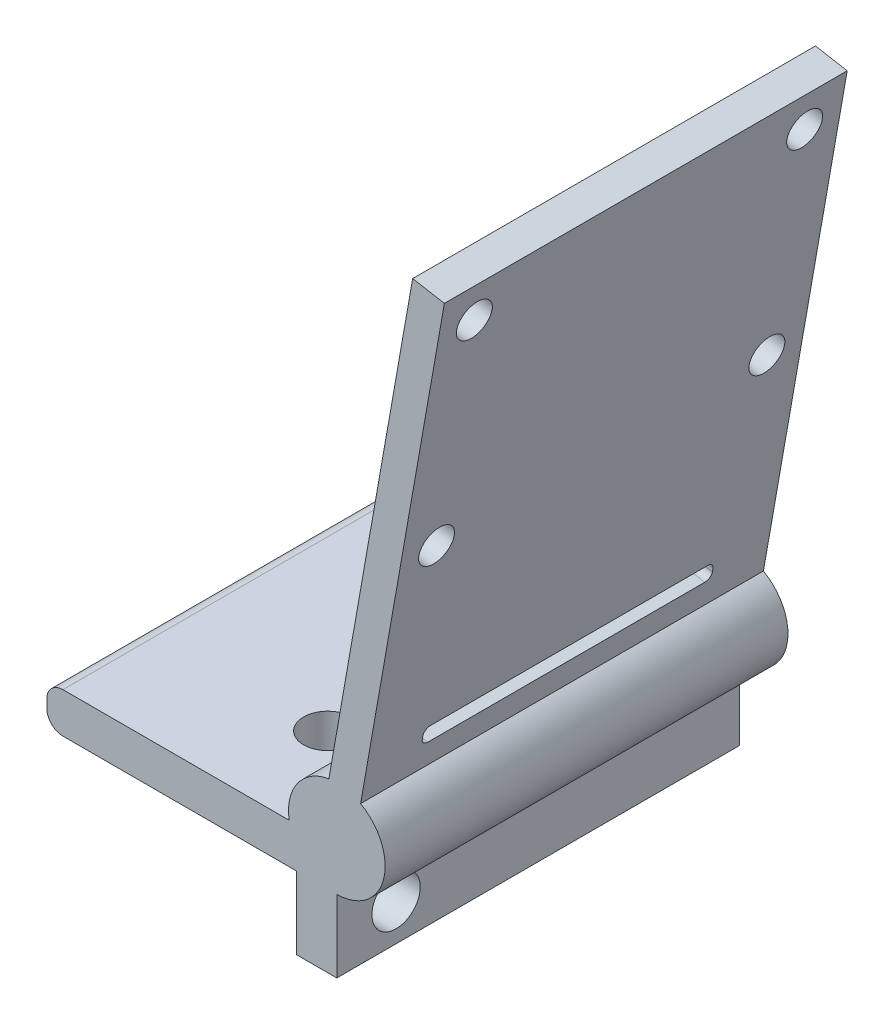
SolidWorks part; units mm, degrees
ref_plane "Front Plane" through (0, 0, 0) normal (0, 0, 1) x (1, 0, 0)
ref_plane "Top Plane" through (0, 0, 0) normal (0, 1, 0) x (1, 0, 0)
ref_plane "Right Plane" through (0, 0, 0) normal (1, 0, 0) x (0, 0, -1)
sketch "Sketch1" plane through (0, 0, 0) normal (0, 0, 1) x (1, 0, 0)
  line L0 (0, -3) -> (0, -0.5)
  line L1 (0, -3) -> (-17, -3)
  line L2 (0, -0.5) -> (-17, -0.5)
  line L3 (-18, -2) -> (-18, -1.5)
  line L4 (6.6753, 32.0985) -> (0.9848, -0.1736)
  line L5 (6.6753, 32.0985) -> (4.7056, 32.4458)
  line L6 (0.9848, -0.1736) -> (-0.9848, 0.1736)
  line L7 (4.7056, 32.4458) -> (-0.9848, 0.1736)
  line L8 (6.6753, 32.0985) -> (-0.9848, 0.1736) construction
  line L9 (0.9848, -0.1736) -> (4.7056, 32.4458) construction
  line L10 (2.8452, 16.1361) -> (0, 0)
  circle A0 centre (0, 0) radius 3
  arc A1 (-18, -2) -> (-17, -3) centre (-17, -2) ccw
  arc A2 (-17, -0.5) -> (-18, -1.5) centre (-17, -1.5) ccw
  point P9 (-18, -3)
  point P13 (2.8452, 16.1361)
  point P19 (0, 0)
  dimension "D1" = 6
  dimension "D4" = 1
  dimension "D5" = 1
  dimension "D2" = 2.5
  dimension "D3" = 18
  dimension "D6" = 2
  dimension "D7" = 32.77
  dimension "D8" = 100
extrude "Boss-Extrude2" add sketch "Sketch1" along normal mid plane 25
sketch "Sketch2" plane through (0.9848, -0.1736, 0) normal (0.9848, -0.1736, 0) x (0, 0, -1)
  line L0 (-12.5, 2.8284) -> (12.5, 2.8284) construction
  line L1 (-8.6, 4.3284) -> (8.6, 4.3284)
  line L2 (-9, 4.7284) -> (-9, 4.9284)
  line L3 (-8.6, 5.3284) -> (8.6, 5.3284)
  line L4 (9, 4.7284) -> (9, 4.9284)
  line L5 (-12.5, 32.77) -> (-12.5, 2.8284) construction
  arc A0 (-8.6, 5.3284) -> (-9, 4.9284) centre (-8.6, 4.9284) ccw
  arc A1 (-8.6, 4.3284) -> (-9, 4.7284) centre (-8.6, 4.7284) cw
  arc A2 (8.6, 5.3284) -> (9, 4.9284) centre (8.6, 4.9284) cw
  arc A3 (9, 4.7284) -> (8.6, 4.3284) centre (8.6, 4.7284) cw
  point P10 (-9, 5.3284)
  point P15 (9, 5.3284)
  point P18 (9, 4.3284)
  dimension "D5" = 0.4
  dimension "D6" = 0.4
  dimension "D7" = 0.4
  dimension "D8" = 0.4
  dimension "D1" = 18
  dimension "D2" = 1
  dimension "D3" = 1.5
  dimension "D4" = 3.5
extrude "Cut-Extrude1" cut sketch "Sketch2" against normal blind 2
sketch "Sketch4" plane through (0, -3, 0) normal (0, -1, 0) x (1, 0, 0)
  circle A0 centre (-6.5627, 6.5) radius 1.5
  circle A1 centre (-6.5627, -6.5) radius 1.5
extrude "Cut-Extrude4" cut sketch "Sketch4" against normal blind 2.5
sketch "Sketch5" plane through (0, 0, 12.5) normal (0, 0, 1) x (1, 0, 0)
  line L1 (0, -3) -> (-2.5, -3)
  line L2 (0, -3) -> (0, -7.5)
  line L3 (0, -7.5) -> (-2.5, -7.5)
  line L4 (-2.5, -3) -> (-2.5, -7.5)
  dimension "D1" = 2.5
  dimension "D2" = 4.5
extrude "Boss-Extrude3" add sketch "Sketch5" against normal blind 25
sketch "Sketch6" plane through (0, 0, 0) normal (1, 0, 0) x (0, 0, -1)
  circle A0 centre (-8.8228, -5.1933) radius 1.5
extrude "Cut-Extrude5" cut sketch "Sketch6" against normal blind 2.5
sketch "Sketch7" plane through (0.9848, -0.1736, 0) normal (0.9848, -0.1736, 0) x (0, 0, -1)
  circle A0 centre (-10.25, 30.52) radius 1.1
  circle A1 centre (-10.25, 17.02) radius 1.1
  circle A2 centre (10.25, 17.02) radius 1.1
  circle A3 centre (10.25, 30.52) radius 1.1
extrude "Cut-Extrude6" cut sketch "Sketch7" against normal blind 2
